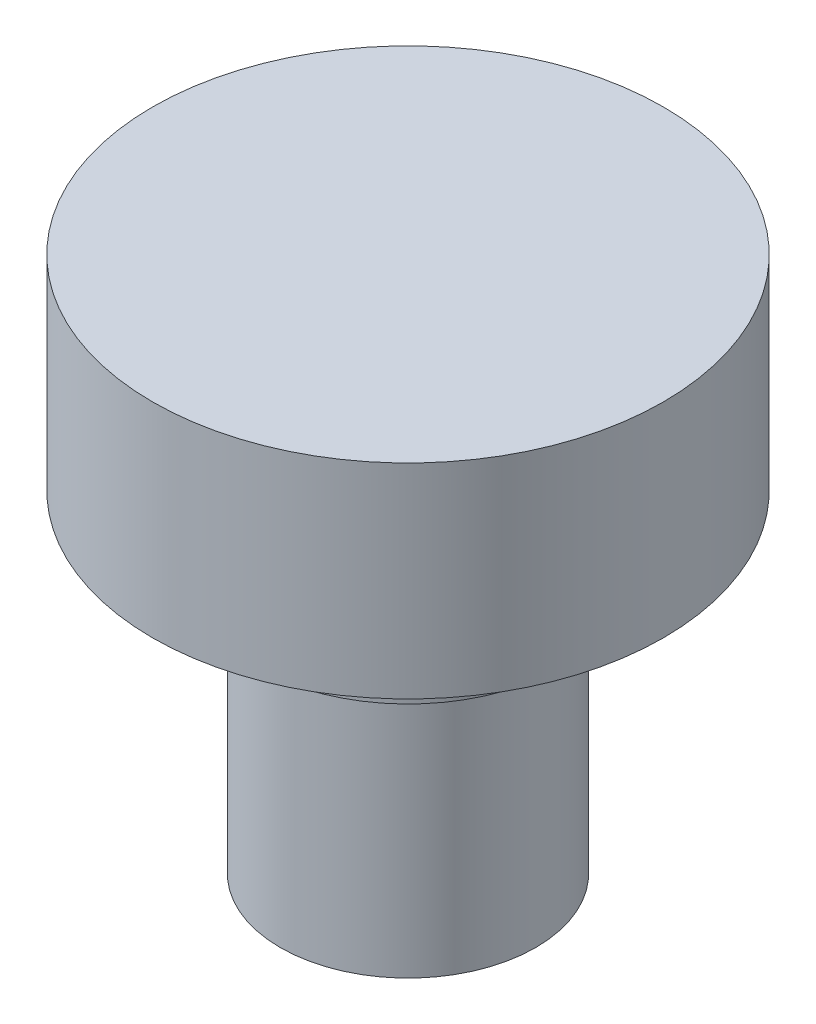
SolidWorks part; units mm, degrees
ref_plane "Plano frontal" through (0, 0, 0) normal (0, 0, 1) x (1, 0, 0)
ref_plane "Plano superior" through (0, 0, 0) normal (0, 1, 0) x (1, 0, 0)
ref_plane "Plano direito" through (0, 0, 0) normal (1, 0, 0) x (0, 0, -1)
sketch "Esboço1" plane through (0, 0, 0) normal (0, 1, 0) x (1, 0, 0)
  circle A4 centre (0, 0) radius 5
  dimension "D1" = 10
extrude "Ressalto-extrusão1" add sketch "Esboço1" along normal blind 4
sketch "Esboço4" plane through (0, 0, 0) normal (0, -1, 0) x (-1, 0, 0)
  circle A0 centre (0, 0) radius 2.5
  dimension "D1" = 5
extrude "Ressalto-extrusão2" add sketch "Esboço4" along normal blind 6.5
sketch "Esboço5" plane through (0, 0, 0) normal (0, -1, 0) x (1, 0, 0)
  circle A0 centre (0, 0) radius 3
  dimension "D1" = 6
extrude "Ressalto-extrusão4" add sketch "Esboço5" along normal blind 1.5
sketch "Esboço6" plane through (0, -6.5, 0) normal (0, -1, 0) x (1, 0, 0)
  point P0 (0, 0)
hole_wizard "Broca de rosquear para tarraxa de M31" positions "3DSketch1" profile "Esboço7" hole size "M3" standard "ISO"
sketch3d "3DSketch1"
  point P0 (0, 0, 0)
  point P3 (0, -6.5, 0)
sketch "Esboço7" plane through (0, -6.5, 0) normal (1, 0, 0) x (0, 0, -1)
  line L0 (0, 0) -> (0, 8.7511)
  line L1 (0, 8.7511) -> (1.25, 8)
  line L2 (1.25, 8) -> (1.25, 0)
  line L5 (1.25, 0) -> (0, 0)
  line L10 (0, 8.7511) -> (-1.25, 8) construction
  line L11 (0, -6.35) -> (0, 107.95) construction
  dimension "Hole Dia." = 2.5
  dimension "Hole Depth" = 8
  dimension "Drill Angle" = 118
